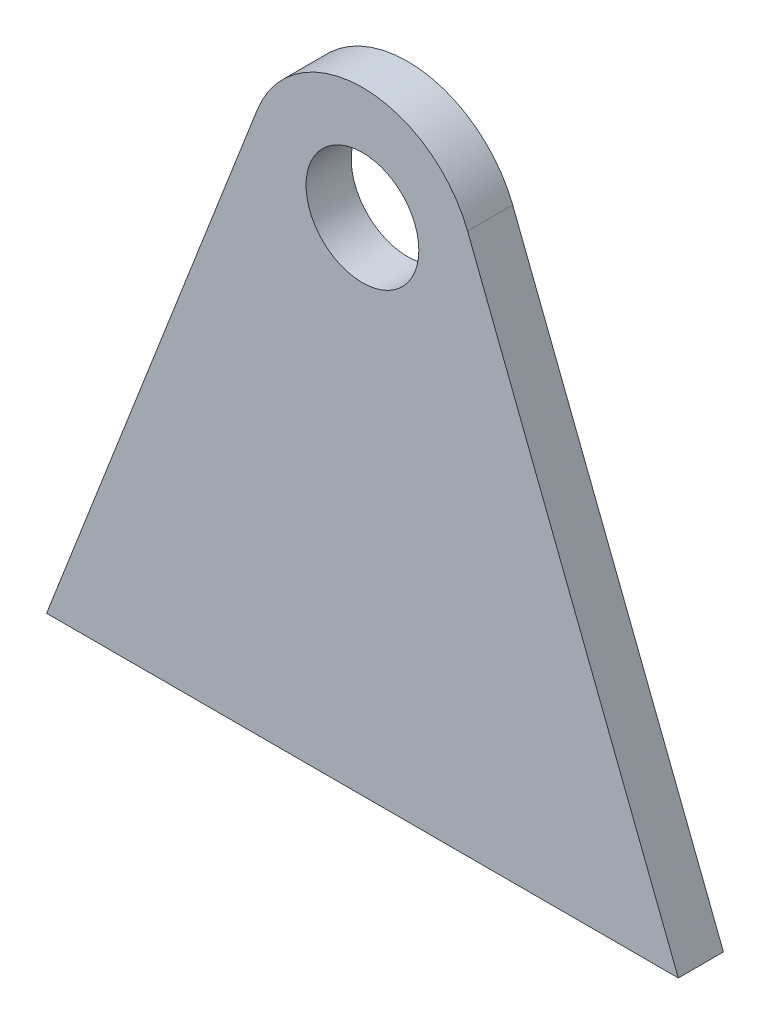
SolidWorks part; units mm, degrees
ref_plane "前基準面" through (0, 0, 0) normal (0, 0, 1) x (1, 0, 0)
ref_plane "上基準面" through (0, 0, 0) normal (0, 1, 0) x (1, 0, 0)
ref_plane "右基準面" through (0, 0, 0) normal (1, 0, 0) x (0, 0, -1)
sketch "草圖1" plane through (0, 0, 0) normal (0, 0, 1) x (1, 0, 0)
  line L0 (0, 0) -> (280, 0)
  line L1 (280, 0) -> (186.5956, 240)
  line L2 (0, 0) -> (93.4044, 240)
  arc A0 (186.5956, 240) -> (93.4044, 240) centre (140, 221.8657) ccw
  circle A1 centre (140, 221.8657) radius 25
  dimension "D1" = 50
  dimension "D5" = 50
  dimension "D2" = 280
  dimension "D3" = 240
  dimension "D4" = 240
extrude "填料-伸長1" add sketch "草圖1" along normal blind 20 contours A1 | L2 A0 L1 L0
